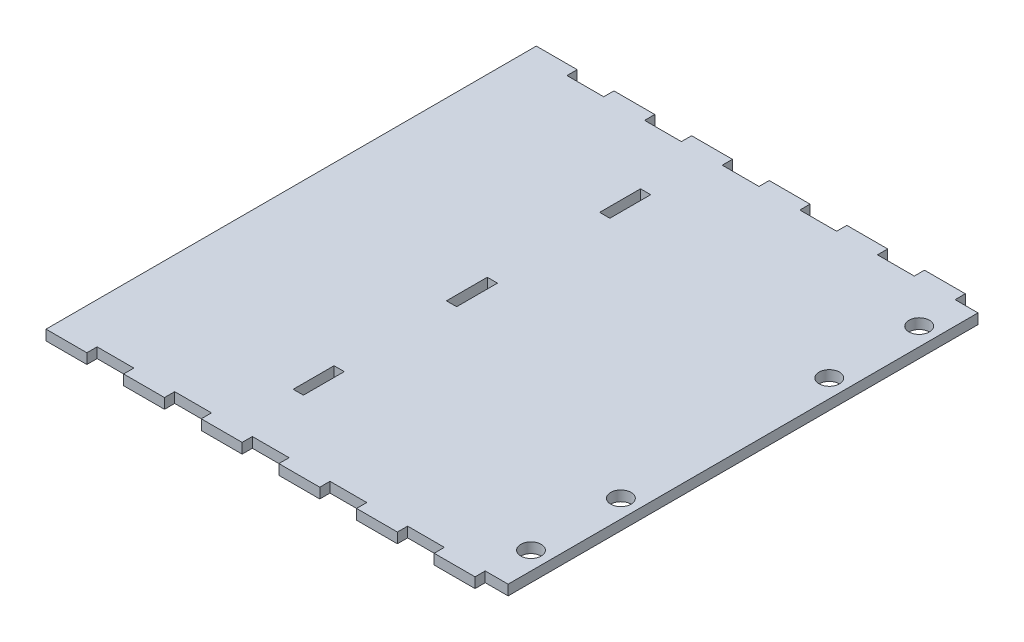
SolidWorks part; units mm, degrees
ref_plane "Front Plane" through (0, 0, 0) normal (0, 0, 1) x (1, 0, 0)
ref_plane "Top Plane" through (0, 0, 0) normal (0, 1, 0) x (1, 0, 0)
ref_plane "Right Plane" through (0, 0, 0) normal (1, 0, 0) x (0, 0, -1)
sketch "Sketch1" plane through (0, 0, 0) normal (0, 1, 0) x (1, 0, 0)
  line L0 (-97.6969, -1.9423) -> (-72.2969, -1.9423)
  line L5 (-72.2969, -1.9423) -> (-72.2969, -8.2923)
  line L8 (-49.4369, -1.9423) -> (-24.0369, -1.9423)
  line L9 (-24.0369, -1.9423) -> (-24.0369, -8.2923)
  line L10 (-24.0369, -8.2923) -> (-1.1769, -8.2923)
  line L11 (-1.1769, -8.2923) -> (-1.1769, -1.9423)
  line L12 (-1.1769, -1.9423) -> (24.2231, -1.9423)
  line L13 (24.2231, -1.9423) -> (24.2231, -8.2923)
  line L16 (47.0831, -1.9423) -> (72.4831, -1.9423)
  line L19 (95.3431, -8.2923) -> (95.3431, -1.9423)
  line L21 (-97.6969, -1.9423) -> (-97.6969, -8.2923)
  line L22 (-97.6969, -8.2923) -> (-120.5569, -8.2923)
  line L26 (134.9671, -8.2923) -> (134.9671, -300.3923)
  line L71 (95.3431, -1.9423) -> (120.7431, -1.9423)
  line L72 (120.7431, -1.9423) -> (120.7431, -8.2923)
  line L73 (120.7431, -8.2923) -> (134.9671, -8.2923)
  line L74 (-120.5569, -300.3923) -> (-97.6969, -300.3923)
  line L75 (-97.6969, -300.3923) -> (-97.6969, -306.7423)
  line L76 (-97.6969, -306.7423) -> (-72.2969, -306.7423)
  line L77 (-72.2969, -306.7423) -> (-72.2969, -300.3923)
  line L78 (-72.2969, -300.3923) -> (-49.4369, -300.3923)
  line L79 (-49.4369, -300.3923) -> (-49.4369, -306.7423)
  line L80 (-49.4369, -306.7423) -> (-24.0369, -306.7423)
  line L81 (-24.0369, -306.7423) -> (-24.0369, -300.3923)
  line L82 (-24.0369, -300.3923) -> (-1.1769, -300.3923)
  line L83 (-1.1769, -300.3923) -> (-1.1769, -306.7423)
  line L84 (-1.1769, -306.7423) -> (24.2231, -306.7423)
  line L85 (24.2231, -306.7423) -> (24.2231, -300.3923)
  line L86 (24.2231, -300.3923) -> (47.0831, -300.3923)
  line L87 (47.0831, -300.3923) -> (47.0831, -306.7423)
  line L88 (47.0831, -306.7423) -> (72.4831, -306.7423)
  line L89 (72.4831, -306.7423) -> (72.4831, -300.3923)
  line L90 (72.4831, -300.3923) -> (95.3431, -300.3923)
  line L91 (95.3431, -300.3923) -> (95.3431, -306.7423)
  line L92 (95.3431, -306.7423) -> (120.7431, -306.7423)
  line L93 (120.7431, -306.7423) -> (120.7431, -300.3923)
  line L94 (120.7431, -300.3923) -> (134.9671, -300.3923)
  line L95 (-49.4369, -1.9423) -> (-49.4369, -8.2923)
  line L96 (-49.4369, -8.2923) -> (-72.2969, -8.2923)
  line L97 (95.3431, -8.2923) -> (72.4831, -8.2923)
  line L98 (72.4831, -8.2923) -> (72.4831, -1.9423)
  line L99 (47.0831, -1.9423) -> (47.0831, -8.2923)
  line L100 (47.0831, -8.2923) -> (24.2231, -8.2923)
  line L102 (-120.5569, -8.2923) -> (-120.5569, -1.9423)
  line L103 (-120.5569, -1.9423) -> (-145.9569, -1.9423)
  line L104 (-145.9569, -1.9423) -> (-145.9569, -8.2923)
  line L108 (-145.9569, -300.3923) -> (-145.9569, -306.7423)
  line L109 (-145.9569, -306.7423) -> (-120.5569, -306.7423)
  line L110 (-120.5569, -306.7423) -> (-120.5569, -300.3923)
  line L111 (-145.9569, -8.2923) -> (-145.9569, -300.3923)
  dimension "D1" = 25.4
  dimension "D2" = 22.86
  dimension "D3" = 14.224
  dimension "D4" = 22.86
  dimension "D5" = 14.224
  dimension "D6" = 25.4
  dimension "D7" = 22.86
  dimension "D8" = 25.4
  dimension "D10" = 22.86
  dimension "D11" = 25.4
extrude "Boss-Extrude1" add sketch "Sketch1" along normal blind 6.35
sketch "Sketch2" plane through (0, 6.35, 0) normal (0, 1, 0) x (1, 0, 0)
  line L0 (134.9671, -8.2923) -> (120.7431, -8.2923) construction
  line L1 (-36.7369, -46.3923) -> (-30.3869, -46.3923)
  line L2 (-36.7369, -46.3923) -> (-36.7369, -71.7923)
  line L3 (-36.7369, -71.7923) -> (-30.3869, -71.7923)
  line L4 (-30.3869, -46.3923) -> (-30.3869, -71.7923)
  line L5 (-36.7369, -236.8923) -> (-30.3869, -236.8923)
  line L6 (-36.7369, -236.8923) -> (-36.7369, -262.2923)
  line L7 (-36.7369, -262.2923) -> (-30.3869, -262.2923)
  line L8 (-30.3869, -236.8923) -> (-30.3869, -262.2923)
  line L9 (-72.2969, -300.3923) -> (-49.4369, -300.3923) construction
  line L10 (-36.7369, -141.6423) -> (-30.3869, -141.6423)
  line L11 (-120.5569, -300.3923) -> (-97.6969, -300.3923) construction
  line L12 (-97.6969, -8.2923) -> (-120.5569, -8.2923) construction
  line L13 (-145.9569, -1.9423) -> (-145.9569, -306.7423) construction
  line L14 (134.9671, -300.3923) -> (134.9671, -8.2923) construction
  line L15 (-36.7369, -141.6423) -> (-36.7369, -167.0423)
  line L16 (120.7431, -300.3923) -> (134.9671, -300.3923) construction
  line L17 (-36.7369, -167.0423) -> (-30.3869, -167.0423)
  line L18 (-30.3869, -141.6423) -> (-30.3869, -167.0423)
  circle A0 centre (123.7911, -274.9923) radius 6.35
  circle A1 centre (123.7911, -33.6923) radius 6.35
  circle A2 centre (123.7911, -89.5723) radius 6.35
  circle A3 centre (123.7911, -219.1123) radius 6.35
  dimension "D7" = 12.7
  dimension "D10" = 12.7
  dimension "D1" = 25.4
  dimension "D2" = 6.35
  dimension "D3" = 38.1
  dimension "D4" = 38.1
  dimension "D5" = 109.22
  dimension "D6" = 109.22
  dimension "D8" = 11.176
  dimension "D9" = 25.4
  dimension "D11" = 11.176
  dimension "D12" = 25.4
  dimension "D13" = 25.4
  dimension "D14" = 6.35
  dimension "D15" = 133.35
  dimension "D16" = 55.88
  dimension "D17" = 55.88
extrude "Cut-Extrude1" cut sketch "Sketch2" against normal through all
